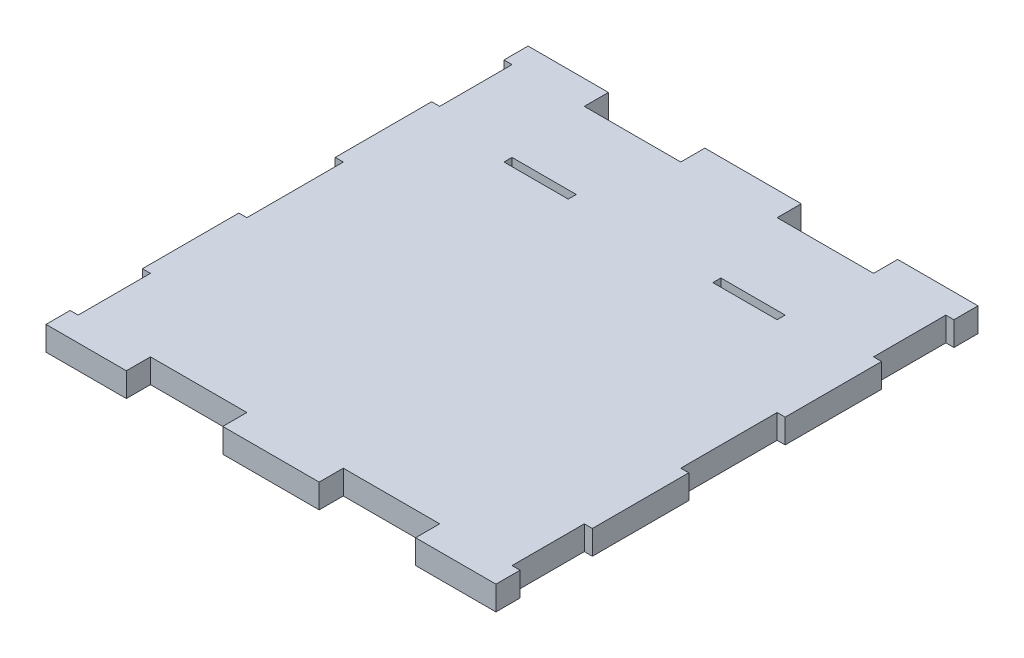
SolidWorks part; units mm, degrees
ref_plane "Front Plane" through (0, 0, 0) normal (0, 0, 1) x (1, 0, 0)
ref_plane "Top Plane" through (0, 0, 0) normal (0, 1, 0) x (1, 0, 0)
ref_plane "Right Plane" through (0, 0, 0) normal (1, 0, 0) x (0, 0, -1)
sketch "Sketch1" plane through (0, 0, 0) normal (0, 1, 0) x (1, 0, 0)
  line L1 (-33.6212, 144.0497) -> (156.8788, 144.0497)
  line L2 (-33.6212, 144.0497) -> (-33.6212, -46.4503)
  line L3 (-33.6212, -46.4503) -> (156.8788, -46.4503)
  line L4 (156.8788, 144.0497) -> (156.8788, -46.4503)
  dimension "D1" = 190.5
  dimension "D2" = 190.5
extrude "Boss-Extrude1" add sketch "Sketch1" along normal blind 9.525
sketch "Sketch2" plane through (0, 9.525, 0) normal (0, 1, 0) x (1, 0, 0)
  line L0 (-33.6212, -46.4503) -> (156.8788, -46.4503) construction
  line L1 (118.7788, -46.4503) -> (80.6788, -46.4503)
  line L2 (118.7788, -46.4503) -> (118.7788, -36.9253)
  line L3 (118.7788, -36.9253) -> (80.6788, -36.9253)
  line L4 (80.6788, -46.4503) -> (80.6788, -36.9253)
  dimension "D1" = 38.1
  dimension "D2" = 9.525
  dimension "D3" = 38.1
extrude "Cut-Extrude1" cut sketch "Sketch2" against normal blind 9.525
sketch "Sketch3" plane through (0, 9.525, 0) normal (0, 1, 0) x (1, 0, 0)
  line L0 (-33.6212, -46.4503) -> (80.6788, -46.4503) construction
  line L1 (42.5788, -46.4503) -> (4.4788, -46.4503)
  line L2 (42.5788, -46.4503) -> (42.5788, -36.9253)
  line L3 (42.5788, -36.9253) -> (4.4788, -36.9253)
  line L4 (4.4788, -46.4503) -> (4.4788, -36.9253)
  dimension "D1" = 38.1
  dimension "D2" = 9.525
  dimension "D3" = 38.1
extrude "Cut-Extrude2" cut sketch "Sketch3" against normal blind 9.525
sketch "Sketch4" plane through (0, 9.525, 0) normal (0, 1, 0) x (1, 0, 0)
  line L0 (156.8788, -46.4503) -> (156.8788, 144.0497) construction
  line L1 (156.8788, -36.9253) -> (147.3538, -36.9253)
  line L2 (156.8788, -36.9253) -> (156.8788, -8.3503)
  line L3 (156.8788, -8.3503) -> (147.3538, -8.3503)
  line L4 (147.3538, -36.9253) -> (147.3538, -8.3503)
  line L5 (118.7788, -46.4503) -> (156.8788, -46.4503) construction
  dimension "D1" = 9.525
  dimension "D2" = 28.575
  dimension "D3" = 9.525
extrude "Cut-Extrude3" cut sketch "Sketch4" against normal blind 9.525
sketch "Sketch5" plane through (0, 9.525, 0) normal (0, 1, 0) x (1, 0, 0)
  line L0 (156.8788, -8.3503) -> (156.8788, 144.0497) construction
  line L1 (156.8788, 29.7497) -> (147.3538, 29.7497)
  line L2 (156.8788, 29.7497) -> (156.8788, 67.8497)
  line L3 (156.8788, 67.8497) -> (147.3538, 67.8497)
  line L4 (147.3538, 29.7497) -> (147.3538, 67.8497)
  line L5 (156.8788, -8.3503) -> (147.3538, -8.3503) construction
  dimension "D1" = 38.1
  dimension "D2" = 9.525
  dimension "D3" = 38.1
extrude "Cut-Extrude4" cut sketch "Sketch5" against normal blind 9.525
sketch "Sketch6" plane through (0, 9.525, 0) normal (0, 1, 0) x (1, 0, 0)
  line L0 (156.8788, 67.8497) -> (156.8788, 144.0497) construction
  line L1 (156.8788, 105.9497) -> (147.3538, 105.9497)
  line L2 (156.8788, 105.9497) -> (156.8788, 134.5247)
  line L3 (156.8788, 134.5247) -> (147.3538, 134.5247)
  line L4 (147.3538, 105.9497) -> (147.3538, 134.5247)
  line L5 (156.8788, 67.8497) -> (147.3538, 67.8497) construction
  dimension "D1" = 38.1
  dimension "D2" = 9.525
  dimension "D3" = 28.575
extrude "Cut-Extrude5" cut sketch "Sketch6" against normal blind 9.525
sketch "Sketch7" plane through (0, 9.525, 0) normal (0, 1, 0) x (1, 0, 0)
  line L0 (156.8788, 144.0497) -> (-33.6212, 144.0497) construction
  line L1 (118.7788, 144.0497) -> (80.6788, 144.0497)
  line L2 (118.7788, 144.0497) -> (118.7788, 134.5247)
  line L3 (118.7788, 134.5247) -> (80.6788, 134.5247)
  line L4 (80.6788, 144.0497) -> (80.6788, 134.5247)
  dimension "D1" = 38.1
  dimension "D2" = 38.1
  dimension "D3" = 9.525
extrude "Cut-Extrude6" cut sketch "Sketch7" against normal blind 9.525
sketch "Sketch8" plane through (0, 9.525, 0) normal (0, 1, 0) x (1, 0, 0)
  line L0 (80.6788, 144.0497) -> (-33.6212, 144.0497) construction
  line L1 (42.5788, 144.0497) -> (4.4788, 144.0497)
  line L2 (42.5788, 144.0497) -> (42.5788, 134.5247)
  line L3 (42.5788, 134.5247) -> (4.4788, 134.5247)
  line L4 (4.4788, 144.0497) -> (4.4788, 134.5247)
  dimension "D1" = 38.1
  dimension "D2" = 9.525
  dimension "D3" = 38.1
extrude "Cut-Extrude7" cut sketch "Sketch8" against normal blind 9.525
sketch "Sketch9" plane through (0, 9.525, 0) normal (0, 1, 0) x (1, 0, 0)
  line L0 (-33.6212, 144.0497) -> (-33.6212, -46.4503) construction
  line L1 (-33.6212, 134.5247) -> (-24.0962, 134.5247)
  line L2 (-33.6212, 134.5247) -> (-33.6212, 105.9497)
  line L3 (-33.6212, 105.9497) -> (-24.0962, 105.9497)
  line L4 (-24.0962, 134.5247) -> (-24.0962, 105.9497)
  dimension "D1" = 9.525
  dimension "D2" = 9.525
  dimension "D3" = 28.575
extrude "Cut-Extrude8" cut sketch "Sketch9" against normal blind 38.1
sketch "Sketch10" plane through (0, 9.525, 0) normal (0, 1, 0) x (1, 0, 0)
  line L0 (-33.6212, 105.9497) -> (-33.6212, -46.4503) construction
  line L1 (-33.6212, 67.8497) -> (-24.0962, 67.8497)
  line L2 (-33.6212, 67.8497) -> (-33.6212, 29.7497)
  line L3 (-33.6212, 29.7497) -> (-24.0962, 29.7497)
  line L4 (-24.0962, 67.8497) -> (-24.0962, 29.7497)
  dimension "D1" = 38.1
  dimension "D2" = 9.525
  dimension "D3" = 38.1
extrude "Cut-Extrude9" cut sketch "Sketch10" against normal blind 9.525
sketch "Sketch11" plane through (0, 9.525, 0) normal (0, 1, 0) x (1, 0, 0)
  line L0 (-33.6212, 29.7497) -> (-33.6212, -46.4503) construction
  line L1 (-33.6212, -8.3503) -> (-24.0962, -8.3503)
  line L2 (-33.6212, -8.3503) -> (-33.6212, -36.9253)
  line L3 (-33.6212, -36.9253) -> (-24.0962, -36.9253)
  line L4 (-24.0962, -8.3503) -> (-24.0962, -36.9253)
  dimension "D1" = 28.575
  dimension "D2" = 9.525
extrude "Cut-Extrude10" cut sketch "Sketch11" against normal blind 9.525
sketch "Sketch12" plane through (0, 9.525, 0) normal (0, 1, 0) x (1, 0, 0)
  line L0 (80.6788, 134.5247) -> (118.7788, 134.5247) construction
  line L1 (7.6538, 102.7747) -> (33.0538, 102.7747)
  line L2 (7.6538, 102.7747) -> (7.6538, 99.5997)
  line L3 (7.6538, 99.5997) -> (33.0538, 99.5997)
  line L4 (33.0538, 102.7747) -> (33.0538, 99.5997)
  line L5 (-24.0962, -36.9253) -> (-24.0962, -8.3503) construction
  line L10 (90.2038, 102.7747) -> (115.6038, 102.7747)
  line L11 (90.2038, 102.7747) -> (90.2038, 99.5997)
  line L12 (90.2038, 99.5997) -> (115.6038, 99.5997)
  line L13 (115.6038, 102.7747) -> (115.6038, 99.5997)
  line L15 (147.3538, -8.3503) -> (147.3538, -36.9253) construction
  line L16 (4.4788, 134.5247) -> (42.5788, 134.5247) construction
  point P4 (20.3538, 99.5997)
  point P5 (33.0538, 101.1872)
  dimension "D1" = 3.175
  dimension "D2" = 25.4
  dimension "D3" = 31.75
  dimension "D4" = 31.75
  dimension "D5" = 3.175
  dimension "D6" = 31.75
  dimension "D7" = 25.4
  dimension "D8" = 31.75
extrude "Cut-Extrude11" cut sketch "Sketch12" against normal blind 12.7
sketch "Sketch15" plane through (0, 9.525, 0) normal (0, 1, 0) x (1, 0, 0)
  line L0 (4.4788, 144.0497) -> (-33.6212, 144.0497) construction
  line L1 (-33.6212, 134.5247) -> (-27.2712, 134.5247)
  line L2 (-33.6212, 134.5247) -> (-33.6212, 144.0497)
  line L3 (-33.6212, 144.0497) -> (-27.2712, 144.0497)
  line L4 (-27.2712, 134.5247) -> (-27.2712, 144.0497)
  point P8 (0, 0)
  dimension "D1" = 6.35
extrude "Cut-Extrude14" cut sketch "Sketch15" against normal through all
sketch "Sketch16" plane through (0, 9.525, 0) normal (0, 1, 0) x (1, 0, 0)
  line L0 (-24.0962, 67.8497) -> (-33.6212, 67.8497) construction
  line L1 (-33.6212, 105.9497) -> (-27.2712, 105.9497)
  line L2 (-33.6212, 105.9497) -> (-33.6212, 67.8497)
  line L3 (-33.6212, 67.8497) -> (-27.2712, 67.8497)
  line L4 (-27.2712, 105.9497) -> (-27.2712, 67.8497)
  line L5 (-24.0962, -8.3503) -> (-33.6212, -8.3503) construction
  line L6 (-33.6212, 29.7497) -> (-27.2712, 29.7497)
  line L7 (-33.6212, 29.7497) -> (-33.6212, -8.3503)
  line L8 (-33.6212, -8.3503) -> (-27.2712, -8.3503)
  line L9 (-27.2712, 29.7497) -> (-27.2712, -8.3503)
  line L10 (-33.6212, -36.9253) -> (-24.0962, -36.9253) construction
  line L11 (-33.6212, -36.9253) -> (-27.2712, -36.9253)
  line L12 (-33.6212, -36.9253) -> (-33.6212, -46.4503)
  line L13 (-33.6212, -46.4503) -> (-27.2712, -46.4503)
  line L14 (-27.2712, -36.9253) -> (-27.2712, -46.4503)
  line L15 (-33.6212, -46.4503) -> (4.4788, -46.4503) construction
  line L16 (147.3538, -36.9253) -> (156.8788, -36.9253) construction
  line L17 (156.8788, -46.4503) -> (150.5288, -46.4503)
  line L18 (156.8788, -46.4503) -> (156.8788, -36.9253)
  line L19 (156.8788, -36.9253) -> (150.5288, -36.9253)
  line L20 (150.5288, -46.4503) -> (150.5288, -36.9253)
  line L21 (147.3538, 29.7497) -> (156.8788, 29.7497) construction
  line L22 (150.5288, 29.7497) -> (156.8788, 29.7497)
  line L23 (150.5288, 29.7497) -> (150.5288, -8.3503)
  line L24 (150.5288, -8.3503) -> (156.8788, -8.3503)
  line L25 (156.8788, 29.7497) -> (156.8788, -8.3503)
  line L26 (156.8788, -8.3503) -> (156.8788, 29.7497) construction
  line L27 (156.8788, -8.3503) -> (147.3538, -8.3503) construction
  line L28 (147.3538, 105.9497) -> (156.8788, 105.9497) construction
  line L29 (156.8788, 67.8497) -> (150.5288, 67.8497)
  line L30 (156.8788, 67.8497) -> (156.8788, 105.9497)
  line L31 (156.8788, 105.9497) -> (150.5288, 105.9497)
  line L32 (150.5288, 67.8497) -> (150.5288, 105.9497)
  line L33 (156.8788, 144.0497) -> (118.7788, 144.0497) construction
  line L34 (156.8788, 134.5247) -> (150.5288, 134.5247)
  line L35 (156.8788, 134.5247) -> (156.8788, 144.0497)
  line L36 (156.8788, 144.0497) -> (150.5288, 144.0497)
  line L37 (150.5288, 134.5247) -> (150.5288, 144.0497)
  dimension "D1" = 6.35
  dimension "D2" = 6.35
  dimension "D3" = 6.35
  dimension "D4" = 6.35
  dimension "D5" = 6.35
  dimension "D6" = 6.35
  dimension "D7" = 6.35
sketch "Sketch19" plane through (0, 9.525, 0) normal (0, 1, 0) x (1, 0, 0)
  line L0 (-33.6212, 105.9497) -> (-24.0962, 105.9497) construction
  line L1 (-33.6212, 67.8497) -> (-27.2712, 67.8497)
  line L2 (-33.6212, 67.8497) -> (-33.6212, 105.9497)
  line L3 (-33.6212, 105.9497) -> (-27.2712, 105.9497)
  line L4 (-27.2712, 67.8497) -> (-27.2712, 105.9497)
  line L5 (-33.6212, 29.7497) -> (-24.0962, 29.7497) construction
  line L6 (-33.6212, -8.3503) -> (-27.2712, -8.3503)
  line L7 (-33.6212, -8.3503) -> (-33.6212, 29.7497)
  line L8 (-33.6212, 29.7497) -> (-27.2712, 29.7497)
  line L9 (-27.2712, -8.3503) -> (-27.2712, 29.7497)
  line L10 (-33.6212, -36.9253) -> (-24.0962, -36.9253) construction
  line L11 (-33.6212, -46.4503) -> (-27.2712, -46.4503)
  line L12 (-33.6212, -46.4503) -> (-33.6212, -36.9253)
  line L13 (-33.6212, -36.9253) -> (-27.2712, -36.9253)
  line L14 (-27.2712, -46.4503) -> (-27.2712, -36.9253)
  line L15 (147.3538, -36.9253) -> (156.8788, -36.9253) construction
  line L16 (156.8788, -46.4503) -> (150.5288, -46.4503)
  line L17 (156.8788, -46.4503) -> (156.8788, -36.9253)
  line L18 (156.8788, -36.9253) -> (150.5288, -36.9253)
  line L19 (150.5288, -46.4503) -> (150.5288, -36.9253)
  line L20 (147.3538, 29.7497) -> (156.8788, 29.7497) construction
  line L21 (156.8788, -8.3503) -> (150.5288, -8.3503)
  line L22 (156.8788, -8.3503) -> (156.8788, 29.7497)
  line L23 (156.8788, 29.7497) -> (150.5288, 29.7497)
  line L24 (150.5288, -8.3503) -> (150.5288, 29.7497)
  line L25 (147.3538, 105.9497) -> (156.8788, 105.9497) construction
  line L26 (156.8788, 67.8497) -> (150.5288, 67.8497)
  line L27 (156.8788, 67.8497) -> (156.8788, 105.9497)
  line L28 (156.8788, 105.9497) -> (150.5288, 105.9497)
  line L29 (150.5288, 67.8497) -> (150.5288, 105.9497)
  line L30 (156.8788, 144.0497) -> (118.7788, 144.0497) construction
  line L31 (156.8788, 134.5247) -> (150.5288, 134.5247)
  line L32 (156.8788, 134.5247) -> (156.8788, 144.0497)
  line L33 (156.8788, 144.0497) -> (150.5288, 144.0497)
  line L34 (150.5288, 134.5247) -> (150.5288, 144.0497)
  dimension "D1" = 6.35
  dimension "D2" = 6.35
  dimension "D3" = 6.35
  dimension "D4" = 6.35
  dimension "D5" = 6.35
  dimension "D6" = 6.35
  dimension "D7" = 6.35
extrude "Cut-Extrude16" cut sketch "Sketch19" against normal through all
extrude "Cut-Extrude15" cut sketch "Sketch16" against normal through all
